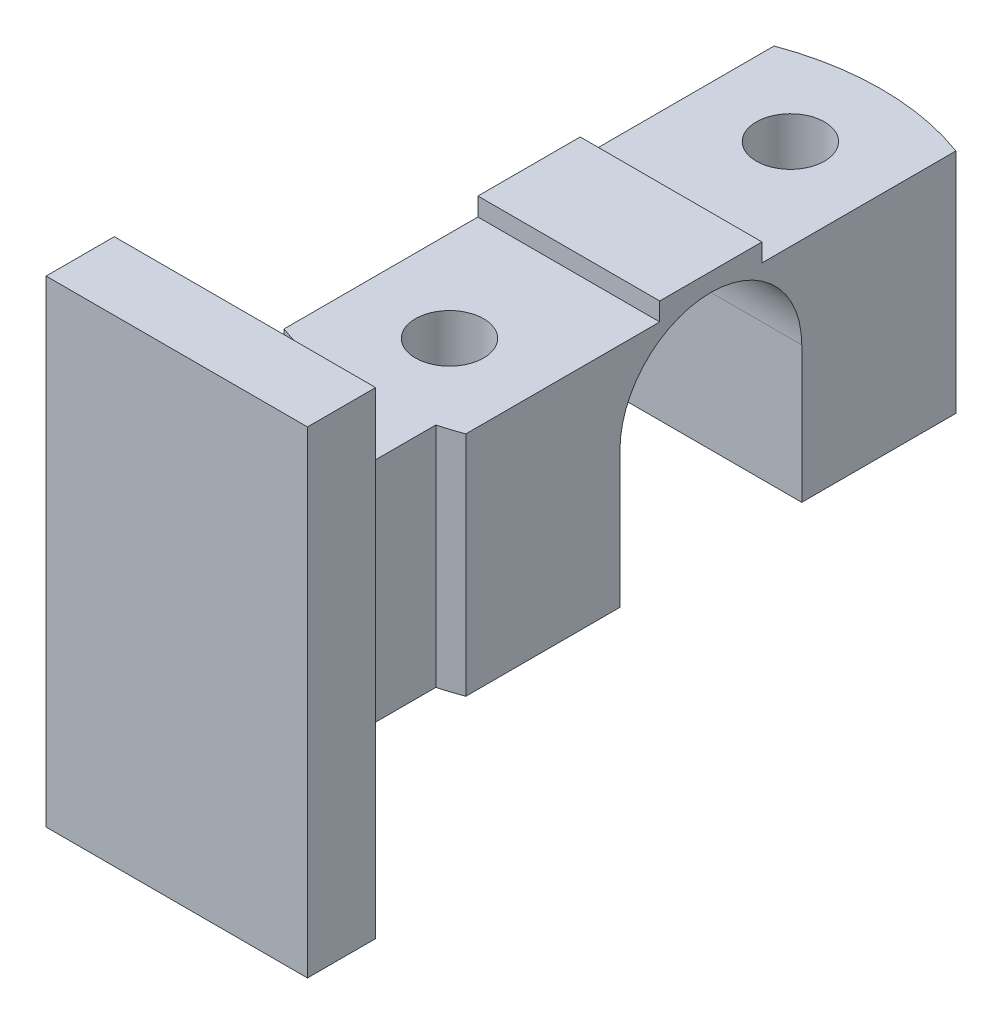
SolidWorks part; units mm, degrees
ref_plane "Front Plane" through (0, 0, 0) normal (0, 0, 1) x (1, 0, 0)
ref_plane "Top Plane" through (0, 0, 0) normal (0, 1, 0) x (1, 0, 0)
ref_plane "Right Plane" through (0, 0, 0) normal (1, 0, 0) x (0, 0, -1)
sketch "Sketch1" plane through (0, 0, 0) normal (0, 0, 1) x (1, 0, 0)
  line L1 (-57.5, 105) -> (57.5, 105)
  line L2 (-57.5, 105) -> (-57.5, -105)
  line L3 (-57.5, -105) -> (57.5, -105)
  line L4 (57.5, 105) -> (57.5, -105)
  line L5 (-57.5, 105) -> (57.5, -105) construction
  line L6 (-57.5, -105) -> (57.5, 105) construction
  point P0 (0, 0)
  dimension "D1" = 210
  dimension "D2" = 115
extrude "Boss-Extrude1" add sketch "Sketch1" along normal blind 30
sketch "Sketch3" plane through (0, 0, 0) normal (0, 1, 0) x (1, 0, 0)
  line L0 (57.5, 0) -> (-57.5, 0) construction
  line L1 (-30, 0) -> (30, 0)
  line L2 (-30, 0) -> (-30, 60)
  line L3 (-30, 60) -> (30, 60)
  line L4 (30, 0) -> (30, 60)
  dimension "D1" = 60
  dimension "D2" = 60
  dimension "D3" = 30
extrude "Boss-Extrude2" add sketch "Sketch3" along normal mid plane 100
sketch "Sketch4" plane through (0, 0, 0) normal (0, 1, 0) x (1, 0, 0)
  line L0 (0, 60) -> (0, 165) construction
  line L1 (30, 60) -> (-30, 60) construction
  line L2 (-40, 272.8193) -> (-40, 57.1807)
  line L3 (40, 272.8193) -> (40, 57.1807)
  arc A0 (-40, 57.1807) -> (40, 57.1807) centre (0, 165) ccw
  arc A1 (40, 272.8193) -> (-40, 272.8193) centre (0, 165) ccw
  circle A3 centre (0, 240) radius 15
  circle A4 centre (0, 90) radius 15
  point P8 (-40, 165)
  point P9 (0, 112.5)
  point P12 (40, 165)
  dimension "D2" = 230
  dimension "D5" = 30
  dimension "D6" = 75
  dimension "D8" = 30
  dimension "D1" = 105
  dimension "D3" = 40
  dimension "D4" = 40
  dimension "D7" = 75
extrude "Boss-Extrude3" add sketch "Sketch4" along normal mid plane 100
fillet "Fillet1" radius 10 4 edges at (-30, 0, 0) (0, -50, 0) (0, 50, 0) (30, 0, 0)
sketch "Sketch7" plane through (-40, 0, 0) normal (-1, 0, 0) x (0, 0, 1)
  line L0 (-345.4988, 10) -> (-122.4135, 10) construction
  line L1 (-165, 50) -> (-165, -81.6363) construction
  line L2 (-272.8193, 50) -> (-57.1807, 50) construction
  line L3 (-205, 10) -> (-205, -50) construction
  line L4 (-272.8193, -50) -> (-57.1807, -50) construction
  line L5 (-125, 10) -> (-125, -50) construction
  line L6 (-205, -50) -> (-125, -50) construction
  line L7 (30, 105) -> (30, -105) construction
  line L8 (-205, -50) -> (-205, 10)
  line L13 (-187.5, 50) -> (-142.5, 50)
  line L14 (-187.5, 50) -> (-187.5, 58)
  line L15 (-187.5, 58) -> (-142.5, 58)
  line L16 (-142.5, 50) -> (-142.5, 58)
  line L17 (-125, 10) -> (-125, -50)
  line L18 (-125, -50) -> (-205, -50)
  arc A0 (-125, 10) -> (-205, 10) centre (-165, 10) ccw construction
  arc A1 (-205, 10) -> (-125, 10) centre (-165, 10) cw
  dimension "D2" = 80
  dimension "D1" = 40
  dimension "D3" = 195
  dimension "D4" = 45
  dimension "D5" = 22.5
  dimension "D6" = 8
extrude "Boss-Extrude6" add sketch "Sketch7" against normal blind 80 contours L15 L16 L14 L13
sketch "Sketch11" plane through (-40, 0, 0) normal (-1, 0, 0) x (0, 0, 1)
  line L0 (-165, -50) -> (-165, 50) construction
  line L1 (-272.8193, -50) -> (-57.1807, -50) construction
  line L2 (-212.6176, 10) -> (-125, 10) construction
  line L3 (-205, 10) -> (-205, -50)
  line L4 (-205, -50) -> (-125, -50)
  line L5 (-125, -50) -> (-125, 10)
  arc A0 (-125, 10) -> (-205, 10) centre (-165, 10) ccw
  point P7 (-122.7368, 10)
  dimension "D1" = 100
  dimension "D2" = 40
extrude "Cut-Extrude1" cut sketch "Sketch11" against normal blind 226 contours L5 A0 L3 L4
